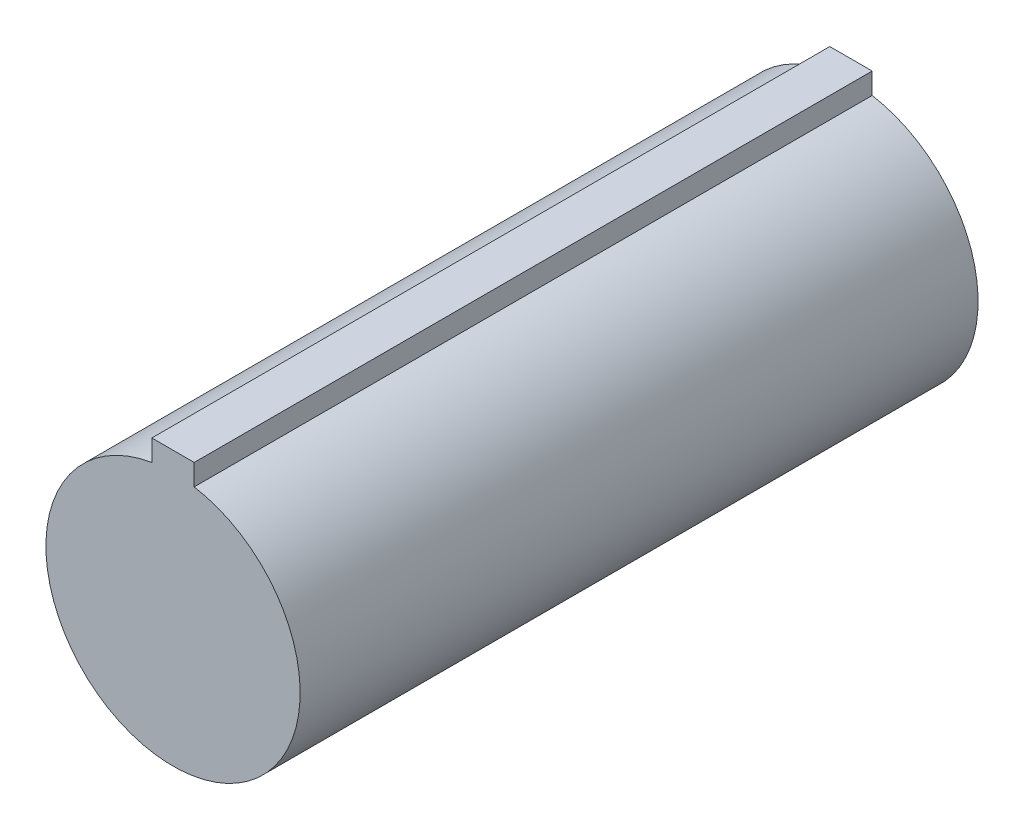
SolidWorks part; units mm, degrees
ref_plane "Front Plane" through (0, 0, 0) normal (0, 0, 1) x (1, 0, 0)
ref_plane "Top Plane" through (0, 0, 0) normal (0, 1, 0) x (1, 0, 0)
ref_plane "Right Plane" through (0, 0, 0) normal (1, 0, 0) x (0, 0, -1)
sketch "Sketch1" plane through (0, 0, 0) normal (0, 0, 1) x (1, 0, 0)
  line L0 (-1.6399, 2.2164) -> (-1.6399, 9.8061) construction
  line L2 (-0.8462, 7.7063) -> (-2.4337, 7.7063)
  line L3 (-0.8462, 7.7063) -> (-0.8462, 6.9125)
  line L4 (-0.8462, 6.9125) -> (-2.4337, 6.9125)
  line L5 (-2.4337, 7.7063) -> (-2.4337, 6.9125)
  line L6 (-0.8462, 7.7063) -> (-2.4337, 6.9125) construction
  line L7 (-0.8462, 6.9125) -> (-2.4337, 7.7063) construction
  circle A0 centre (-1.6399, 2.2164) radius 4.7625
  point P2 (-1.6399, 7.3094)
  dimension "D1" = 9.525
  dimension "D2" = 0.7937
  dimension "D3" = 1.5875
extrude "Boss-Extrude1" add sketch "Sketch1" along normal blind 25.4 contours L4 A0
